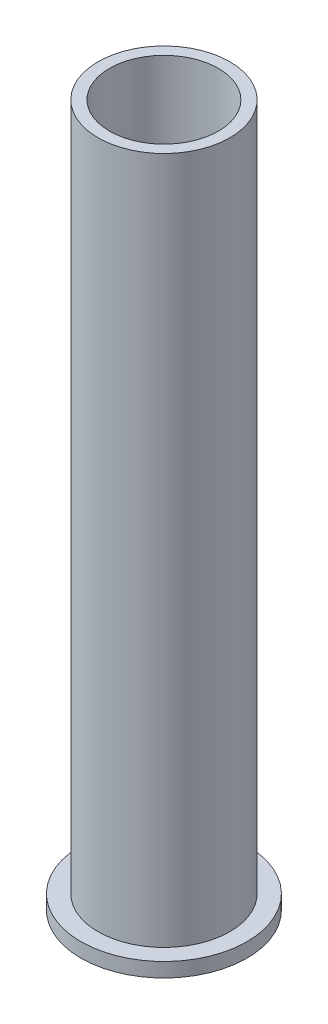
SolidWorks part; units mm, degrees
ref_plane "Front Plane" through (0, 0, 0) normal (0, 0, 1) x (1, 0, 0)
ref_plane "Top Plane" through (0, 0, 0) normal (0, 1, 0) x (1, 0, 0)
ref_plane "Right Plane" through (0, 0, 0) normal (1, 0, 0) x (0, 0, -1)
sketch "Sketch1" plane through (0, 0, 0) normal (0, 1, 0) x (1, 0, 0)
  circle A0 centre (0, 0) radius 12.065
  circle A1 centre (0, 0) radius 18.415
  dimension "D1" = 24.13
  dimension "D2" = 6.35
extrude "Boss-Extrude1" add sketch "Sketch1" along normal blind 3.175
sketch "Sketch2" plane through (0, 3.175, 0) normal (0, 1, 0) x (1, 0, 0)
  circle A0 centre (0, 0) radius 12.065
  circle A1 centre (0, 0) radius 14.605
  dimension "D1" = 24.13
  dimension "D2" = 2.54
extrude "Boss-Extrude2" add sketch "Sketch2" along normal blind 152.4
